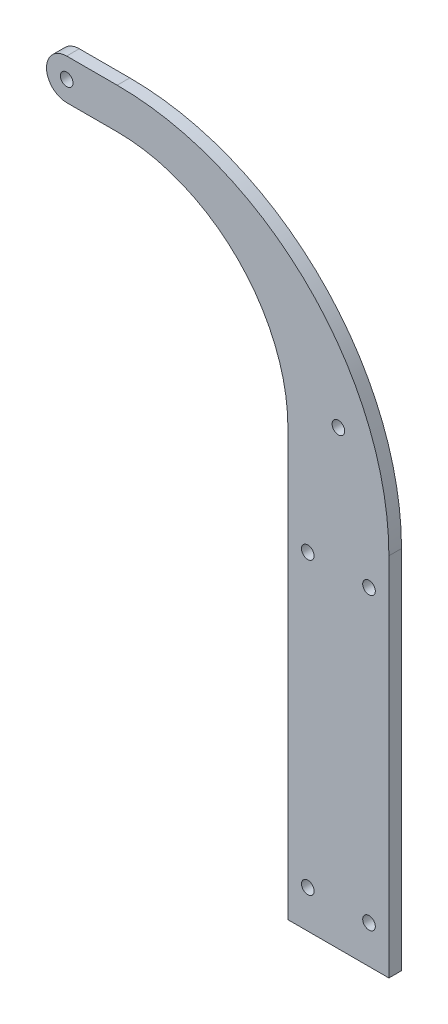
SolidWorks part; units mm, degrees
ref_plane "Front Plane" through (0, 0, 0) normal (0, 0, 1) x (1, 0, 0)
ref_plane "Top Plane" through (0, 0, 0) normal (0, 1, 0) x (1, 0, 0)
ref_plane "Right Plane" through (0, 0, 0) normal (1, 0, 0) x (0, 0, -1)
sketch "Sketch1" plane through (0, 0, 0) normal (0, 0, 1) x (1, 0, 0)
  line L0 (0, 10.16) -> (25.4, 10.16)
  line L1 (0, -10.16) -> (25.4, -10.16)
  line L2 (111.3, -96.06) -> (111.3, -310.4822)
  line L3 (111.3, -310.4822) -> (162.1, -310.4822)
  line L4 (162.1, -310.4822) -> (162.1, -126.54)
  line L6 (25.4, -10.16) -> (25.4, 10.16) construction
  line L9 (121.3, -291.4322) -> (121.3, -145.3822) construction
  line L10 (121.3, -145.3822) -> (152.1, -145.3822) construction
  line L11 (152.1, -145.3822) -> (152.1, -291.4322) construction
  line L12 (121.3, -291.4322) -> (152.1, -291.4322) construction
  arc A0 (0, 10.16) -> (0, -10.16) centre (0, 0) ccw
  circle A1 centre (0, 0) radius 3.175
  arc A3 (25.4, 10.16) -> (162.1, -126.54) centre (25.4, -126.54) cw
  arc A4 (25.4, -10.16) -> (111.3, -96.06) centre (25.4, -96.06) cw
  circle A6 centre (136.7, -83.36) radius 3.175
  circle A7 centre (121.3, -291.4322) radius 3.175
  circle A8 centre (152.1, -291.4322) radius 3.175
  circle A9 centre (121.3, -145.3822) radius 3.175
  circle A10 centre (152.1, -145.3822) radius 3.175
  point P17 (111.3, -107.2822)
  dimension "D1" = 20.32
  dimension "D2" = 6.35
  dimension "D3" = 6.35
  dimension "D4" = 25.4
  dimension "D7" = 136.7
  dimension "D9" = 19.05
  dimension "D5" = 203.2
  dimension "D6" = 50.8
  dimension "D8" = 300.3222
  dimension "D10" = 165.1
  dimension "D11" = 227.1222
  dimension "D12" = 25.4
  dimension "D13" = 10
  dimension "D14" = 10
extrude "Boss-Extrude1" add sketch "Sketch1" along normal blind 6.35
